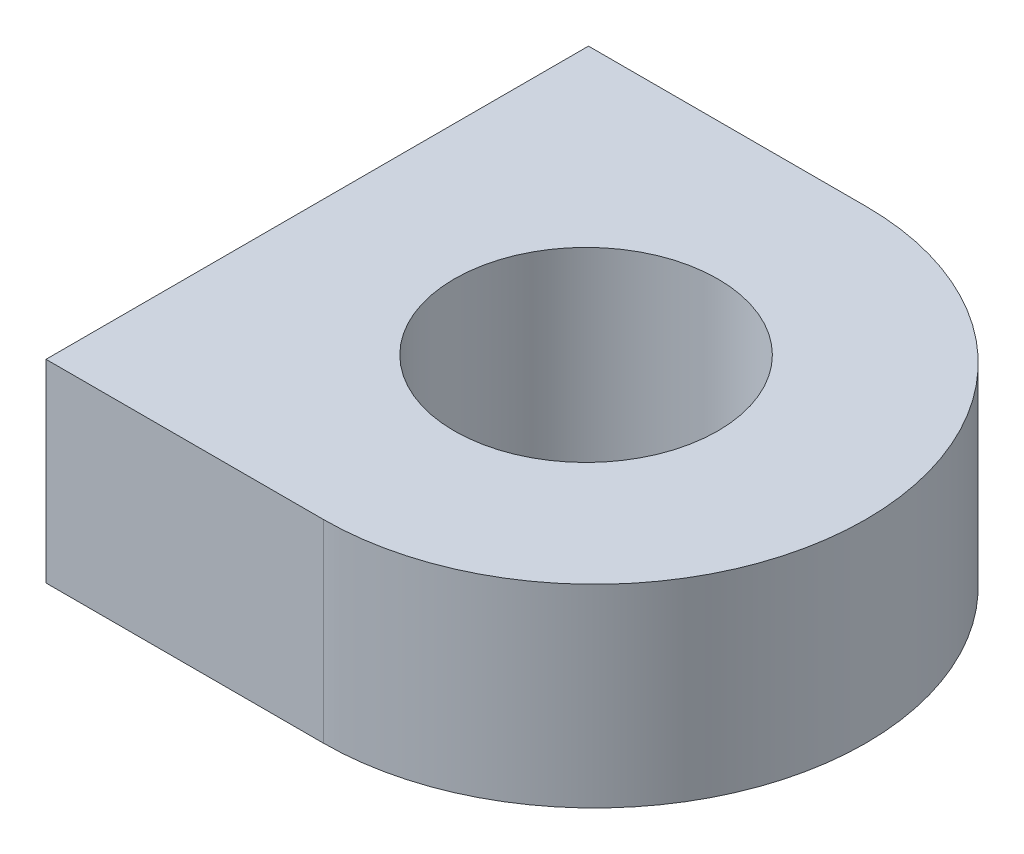
SolidWorks part; units mm, degrees
ref_plane "Front Plane" through (0, 0, 0) normal (0, 0, 1) x (1, 0, 0)
ref_plane "Top Plane" through (0, 0, 0) normal (0, 1, 0) x (1, 0, 0)
ref_plane "Right Plane" through (0, 0, 0) normal (1, 0, 0) x (0, 0, -1)
sketch "Sketch1" plane through (0, 0, 0) normal (0, 1, 0) x (1, 0, 0)
  line L0 (-3.4358, -0.0334) -> (-3.4358, 3.4666)
  line L1 (-3.4358, -0.0334) -> (-3.4358, -3.5334)
  line L5 (-3.4358, -3.5334) -> (0.1437, -3.5334)
  line L6 (-3.4358, 3.4666) -> (0.1437, 3.4666)
  circle A2 centre (0, 0) radius 1.7
  arc A4 (0.1437, 3.4666) -> (0.1437, -3.5334) centre (0.1437, -0.0334) cw
  dimension "D1" = 3.4
  dimension "D2" = 3.5
extrude "Boss-Extrude2" add sketch "Sketch1" along normal blind 2.5
